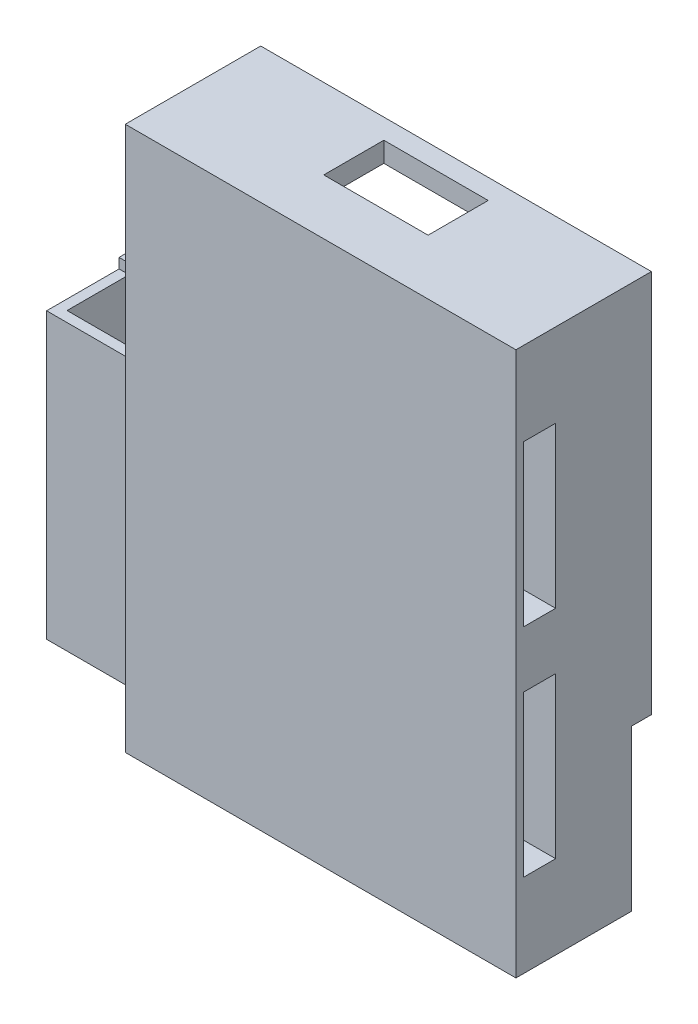
SolidWorks part; units mm, degrees
ref_plane "Front Plane" through (0, 0, 0) normal (0, 0, 1) x (1, 0, 0)
ref_plane "Top Plane" through (0, 0, 0) normal (0, 1, 0) x (1, 0, 0)
ref_plane "Right Plane" through (0, 0, 0) normal (1, 0, 0) x (0, 0, -1)
sketch "Sketch1" plane through (0, 0, 0) normal (0, 1, 0) x (1, 0, 0)
  line L0 (0, 0) -> (0, 60.439) construction
  line L1 (0, 0) -> (86.9706, 0) construction
  line L2 (-30.9499, -3.4771) -> (30.9499, -3.4771)
  line L4 (27.7749, 5.2859) -> (-27.7749, 5.2859)
  line L7 (-30.9499, 17.9859) -> (-24.0411, 17.9859)
  line L8 (-24.0411, 17.9859) -> (-24.0411, 14.8109)
  line L9 (-24.0411, 14.8109) -> (-27.7749, 14.8109)
  line L10 (-27.7749, 14.8109) -> (-27.7749, 5.2859)
  line L11 (24.0411, 14.8109) -> (27.7749, 14.8109)
  line L12 (27.7749, 14.8109) -> (27.7749, 5.2859)
  line L14 (30.9499, 17.9859) -> (24.0411, 17.9859)
  line L15 (24.0411, 17.9859) -> (24.0411, 14.8109)
  line L16 (-30.9499, 17.9859) -> (-30.9499, -3.4771)
  line L17 (30.9499, 17.9859) -> (30.9499, -3.4771)
  dimension "D1" = 61.8998
  dimension "D2" = 3.175
  dimension "D3" = 8.763
  dimension "D4" = 6.9088
  dimension "D5" = 27.7749
  dimension "D6" = 9.525
extrude "Boss-Extrude1" add sketch "Sketch1" along normal blind 83.0326 contours L14 L15 L11 L12 L4 L10 L9 L8 L7 L16 L2 L17
sketch "Sketch6" plane through (0, 83.0326, 0) normal (0, 1, 0) x (1, 0, 0)
  line L0 (-30.9499, 17.9859) -> (-30.9499, -3.4771)
  line L1 (-30.9499, -3.4771) -> (30.9499, -3.4771)
  line L2 (30.9499, -3.4771) -> (30.9499, 17.9859)
  line L3 (30.9499, 17.9859) -> (-30.9499, 17.9859)
extrude "Boss-Extrude3" add sketch "Sketch6" along normal blind 3.175
sketch "Sketch7" plane through (0, 83.0326, 0) normal (0, -1, 0) x (1, 0, 0)
  line L0 (0, -5.2859) -> (0, -14.8109) construction
  line L1 (27.7749, -5.2859) -> (-27.7749, -5.2859) construction
  line L2 (-8.2677, -5.2859) -> (-8.2677, -14.8109)
  line L3 (8.2677, -5.2859) -> (8.2677, -14.8109)
  line L4 (8.2677, -14.8109) -> (-8.2677, -14.8109)
  line L5 (8.2677, -5.2859) -> (-8.2677, -5.2859)
  dimension "D1" = 9.525
  dimension "D2" = 8.2677
  dimension "D3" = 8.2677
extrude "Cut-Extrude2" cut sketch "Sketch7" against normal through all
sketch "Sketch8" plane through (-30.9499, 0, 0) normal (-1, 0, 0) x (0, 0, 1)
  line L0 (-17.9859, 43.1038) -> (3.4771, 43.1038) construction
  line L1 (-17.9859, 86.2076) -> (-17.9859, 0) construction
  line L2 (3.4771, 86.2076) -> (3.4771, 0) construction
  line L4 (2.2655, 13.224) -> (2.2655, 38.624)
  line L6 (-0.4599, 43.1038) -> (-0.4599, 24.0538) construction
  line L7 (2.2655, 13.224) -> (-2.8145, 13.224)
  line L8 (2.2655, 72.9836) -> (-2.8145, 72.9836)
  line L9 (2.2655, 72.9836) -> (2.2655, 47.5836)
  line L10 (2.2655, 47.5836) -> (-2.8145, 47.5836)
  line L11 (-2.8145, 72.9836) -> (-2.8145, 47.5836)
  line L14 (-2.8145, 13.224) -> (-2.8145, 38.624)
  line L15 (2.2655, 38.624) -> (-2.8145, 38.624)
  point P8 (2.2655, 60.2836)
  point P21 (2.2655, 25.924)
  dimension "D3" = 5.08
  dimension "D4" = 25.4
extrude "Cut-Extrude3" cut sketch "Sketch8" against normal through all contours L8 L11 L10 L9 | L4 L15 L14 L7
sketch "Sketch14" plane through (0, 0, 0) normal (0, -1, 0) x (1, 0, 0)
  line L0 (-27.7749, -5.2859) -> (-30.9499, -5.2859) construction
  line L1 (-30.9499, -17.9859) -> (-30.9499, 3.4771) construction
sketch "Sketch15" plane through (-30.9499, 0, 0) normal (-1, 0, 0) x (0, 0, 1)
  line L2 (-5.8144, 45.085) -> (-33.5385, 45.085)
  line L3 (-33.5385, 45.085) -> (-33.5385, 0)
  line L6 (-5.8144, 0) -> (-33.5385, 0)
  line L7 (-5.8144, 45.085) -> (-5.8144, 0)
  dimension "D1" = 27.7241
  dimension "D2" = 27.7241
extrude "Boss-Extrude5" add sketch "Sketch15" along normal blind 3.175
sketch "Sketch21" plane through (-34.1249, 0, 0) normal (-1, 0, 0) x (0, 0, 1)
  line L0 (-19.6765, 45.085) -> (-19.6765, 0) construction
  line L1 (-5.8144, 45.085) -> (-33.5385, 45.085) construction
  line L2 (-33.5385, 0) -> (-5.8144, 0) construction
  line L3 (-5.8144, 0) -> (-5.8144, 45.085) construction
  line L4 (-33.5385, 45.085) -> (-33.5385, 0) construction
  line L5 (-5.8144, 45.085) -> (-5.8144, 0)
  line L6 (-5.8144, 0) -> (-7.4654, 0)
  line L7 (-7.4654, 0) -> (-7.4654, 45.085)
  line L8 (-7.4654, 45.085) -> (-5.8144, 45.085)
  dimension "D1" = 1.651
extrude "Boss-Extrude10" add sketch "Sketch21" along normal blind 16.9926
sketch "Sketch22" plane through (0, 0, -33.5385) normal (0, 0, -1) x (-1, 0, 0)
  line L0 (30.9499, 45.085) -> (51.1175, 45.085)
  line L1 (51.1175, 45.085) -> (51.1175, 0)
  line L2 (51.1175, 0) -> (30.9499, 0)
  line L3 (30.9499, 0) -> (30.9499, 45.085)
extrude "Boss-Extrude11" add sketch "Sketch22" along normal blind 1.5875
sketch "Sketch23" plane through (-51.1175, 0, 0) normal (-1, 0, 0) x (0, 0, 1)
  line L0 (-35.126, 45.085) -> (-5.8144, 45.085)
  line L1 (-5.8144, 45.085) -> (-5.8144, 0)
  line L2 (-5.8144, 0) -> (-35.126, 0)
  line L3 (-35.126, 0) -> (-35.126, 45.085)
extrude "Boss-Extrude12" add sketch "Sketch23" along normal blind 1.5875
sketch "Sketch24" plane through (0, 45.085, 0) normal (0, 1, 0) x (1, 0, 0)
  line L0 (-52.705, 20.4702) -> (-30.9499, 20.4702) construction
  line L1 (-52.705, 5.8144) -> (-52.705, 35.126) construction
  line L2 (-30.9499, 17.9859) -> (-30.9499, 35.126) construction
  line L3 (-52.705, 17.2952) -> (-30.9499, 17.2952)
  line L4 (-52.705, 23.6452) -> (-30.9499, 23.6452)
  line L5 (-52.705, 23.6452) -> (-52.705, 17.2952)
  line L6 (-30.9499, 17.2952) -> (-30.9499, 23.6452)
  dimension "D1" = 3.175
  dimension "D2" = 3.175
extrude "Boss-Extrude13" add sketch "Sketch24" along normal blind 1.5875
sketch "Sketch25" plane through (0, 0, -17.9859) normal (0, 0, -1) x (-1, 0, 0)
  line L0 (-30.9499, 0) -> (-30.9499, 25.4)
  line L1 (-30.9499, 86.2076) -> (-30.9499, 0) construction
  line L2 (-30.9499, 25.4) -> (30.9499, 25.4)
  line L3 (30.9499, 46.6725) -> (30.9499, 0) construction
  line L4 (30.9499, 25.4) -> (30.9499, 0)
  line L5 (30.9499, 0) -> (-30.9499, 0)
  dimension "D1" = 25.4
extrude "Cut-Extrude4" cut sketch "Sketch25" against normal blind 3.175
equation "\"1.0921.1120754in\"=1.11208"
equation "\"0.0625in..6690\"=0.0625"
